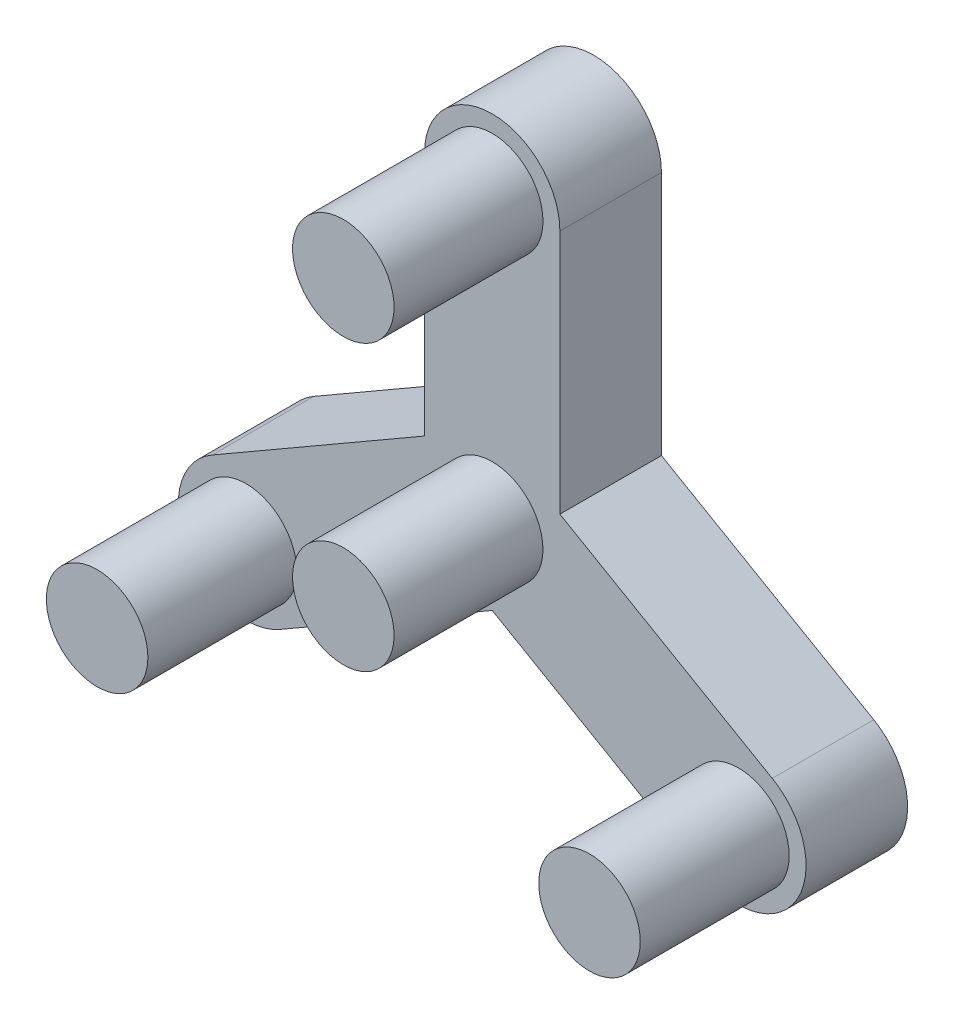
SolidWorks part; units mm, degrees
ref_plane "Front Plane" through (0, 0, 0) normal (0, 0, 1) x (1, 0, 0)
ref_plane "Top Plane" through (0, 0, 0) normal (0, 1, 0) x (1, 0, 0)
ref_plane "Right Plane" through (0, 0, 0) normal (1, 0, 0) x (0, 0, -1)
sketch "Sketch1" plane through (0, 0, 0) normal (0, 0, 1) x (1, 0, 0)
  line L0 (0, 0) -> (-56.8717, -32.8349) construction
  line L1 (0, 0) -> (36.3731, -21) construction
  line L2 (0, 0) -> (0, 42) construction
  line L7 (0, -11.547) -> (-31.3731, -29.6603)
  line L8 (-10, 5.7735) -> (-41.3731, -12.3397)
  line L11 (0, -11.547) -> (31.3731, -29.6603)
  line L12 (10, 5.7735) -> (10, 42)
  line L13 (10, 5.7735) -> (41.3731, -12.3397)
  line L14 (-10, 5.7735) -> (-10, 42)
  arc A1 (10, 42) -> (-10, 42) centre (0, 42) ccw
  arc A3 (-41.3731, -12.3397) -> (-31.3731, -29.6603) centre (-36.3731, -21) ccw
  arc A5 (31.3731, -29.6603) -> (41.3731, -12.3397) centre (36.3731, -21) ccw
  point P6 (0, 0)
  point P12 (0, 0)
  point P18 (0, 0)
  dimension "D4" = 10
  dimension "D8" = 42
  dimension "D9" = 42
  dimension "D10" = 42
extrude "Carrier Base" add sketch "Sketch1" along normal mid plane 15 contours L14 A1 L12 L13 A5 L11 L7 A3 L8
sketch "Sketch3" plane through (0, 0, 7.5) normal (0, 0, 1) x (1, 0, 0)
  circle A0 centre (0, 42) radius 7.5
  circle A1 centre (36.3731, -21) radius 7.5
  circle A2 centre (-36.3731, -21) radius 7.5
  dimension "D1" = 15
extrude "Planet Shafts" add sketch "Sketch3" along normal blind 22
sketch "Sketch4" plane through (0, 0, 7.5) normal (0, 0, 1) x (1, 0, 0)
  circle A0 centre (0, 0) radius 7.5
  dimension "D1" = 15
extrude "Sun Shaft" add sketch "Sketch4" along normal blind 22
